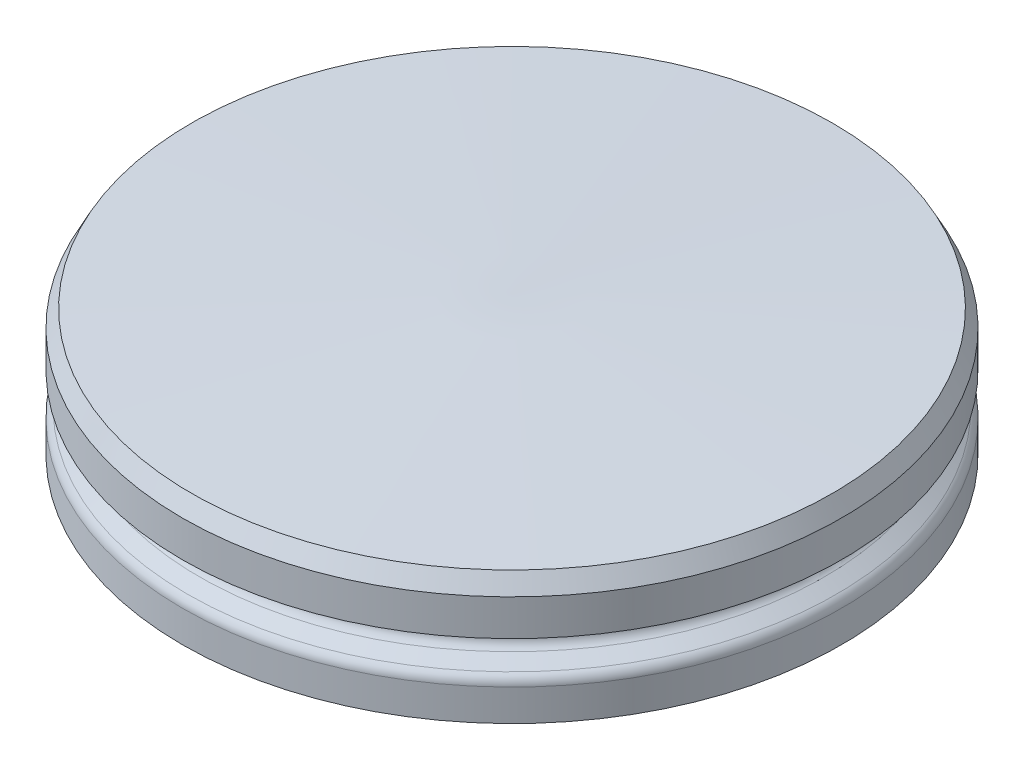
SolidWorks part; units mm, degrees
ref_plane "Front Plane" through (0, 0, 0) normal (0, 0, 1) x (1, 0, 0)
ref_plane "Top Plane" through (0, 0, 0) normal (0, 1, 0) x (1, 0, 0)
ref_plane "Right Plane" through (0, 0, 0) normal (1, 0, 0) x (0, 0, -1)
sketch "Sketch1" plane through (0, 0, 0) normal (0, 0, 1) x (1, 0, 0)
  line L0 (0, 0) -> (70.2492, -2.773)
  line L1 (70.2492, -2.773) -> (70.2492, -14.0292)
  line L2 (70.2492, -14.0292) -> (61.5841, -15.4734)
  line L3 (61.5841, -15.4734) -> (70.2492, -21.6627)
  line L4 (70.2492, -21.6627) -> (70.2492, -29.7089)
  line L5 (70.2492, -29.7089) -> (0, -26.9359)
  line L6 (0, -26.9359) -> (0, 0)
  dimension "D1" = 45
revolve "Revolve1" add sketch "Sketch1" angle 360 about L6
fillet "Fillet1" radius 2.54 2 edges at (0, -21.6627, -70.2492) (0, -15.4734, -61.5841)
chamfer "Chamfer1" distance 1.905 angle 60 1 edges at (0, -2.773, -70.2492)
